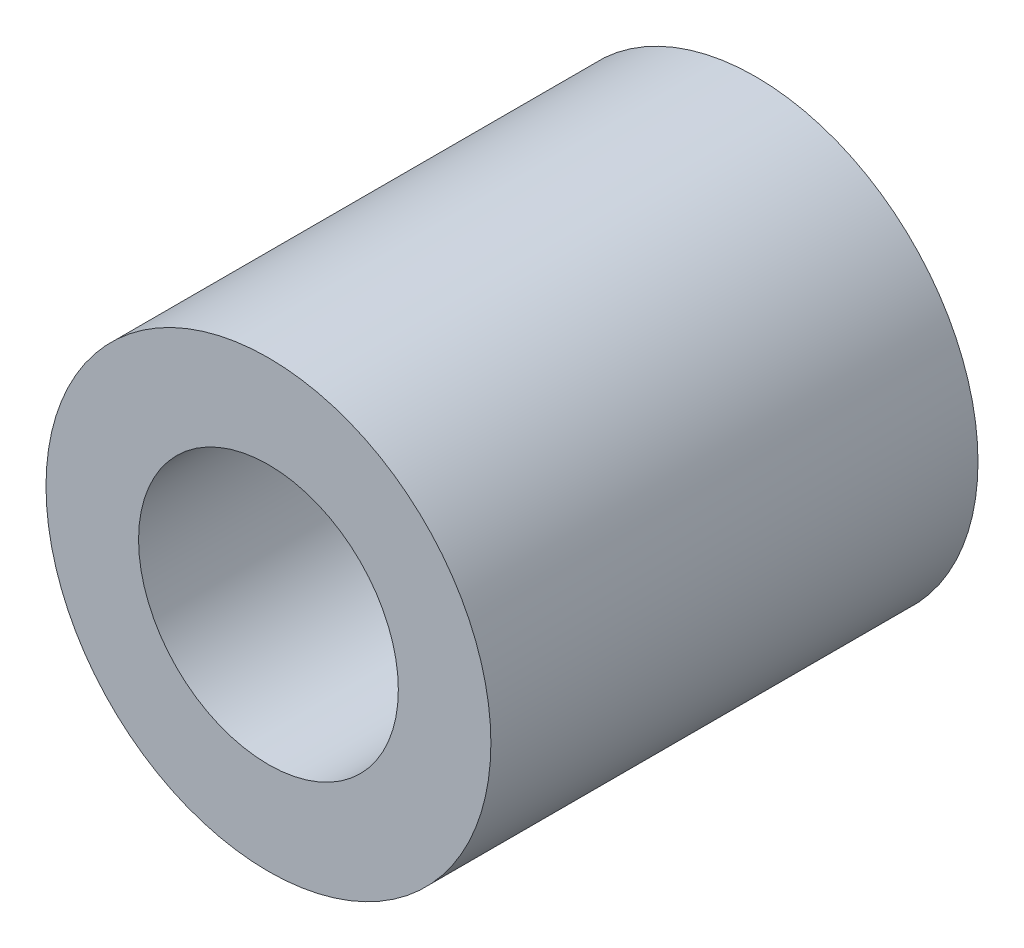
SolidWorks part; units mm, degrees
ref_plane "Front Plane" through (0, 0, 0) normal (0, 0, 1) x (1, 0, 0)
ref_plane "Top Plane" through (0, 0, 0) normal (0, 1, 0) x (1, 0, 0)
ref_plane "Right Plane" through (0, 0, 0) normal (1, 0, 0) x (0, 0, -1)
sketch "Sketch1" plane through (0, 0, 0) normal (0, 0, 1) x (1, 0, 0)
  circle A0 centre (0, 0) radius 6.85
  circle A1 centre (0, 0) radius 4
extrude "Boss-Extrude1" add sketch "Sketch1" along normal blind 15
